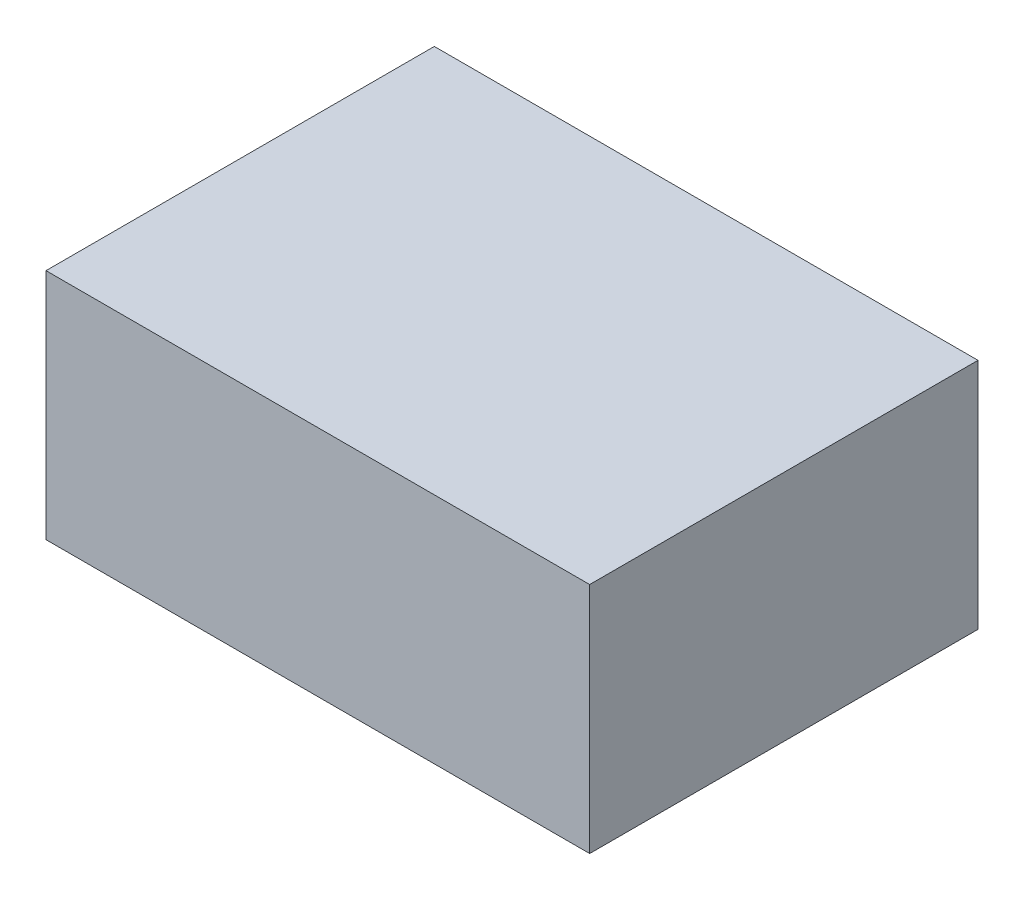
SolidWorks part; units mm, degrees
ref_plane "前视基准面" through (0, 0, 0) normal (0, 0, 1) x (1, 0, 0)
ref_plane "上视基准面" through (0, 0, 0) normal (0, 1, 0) x (1, 0, 0)
ref_plane "右视基准面" through (0, 0, 0) normal (1, 0, 0) x (0, 0, -1)
sketch "草图1" plane through (0, 0, 0) normal (0, 1, 0) x (1, 0, 0)
  line L1 (-35, 25) -> (35, 25)
  line L2 (-35, 25) -> (-35, -25)
  line L3 (-35, -25) -> (35, -25)
  line L4 (35, 25) -> (35, -25)
  dimension "D1" = 50
  dimension "D2" = 70
  dimension "D3" = 35
  dimension "D4" = 25
extrude "凸台-拉伸1" add sketch "草图1" along normal blind 30
